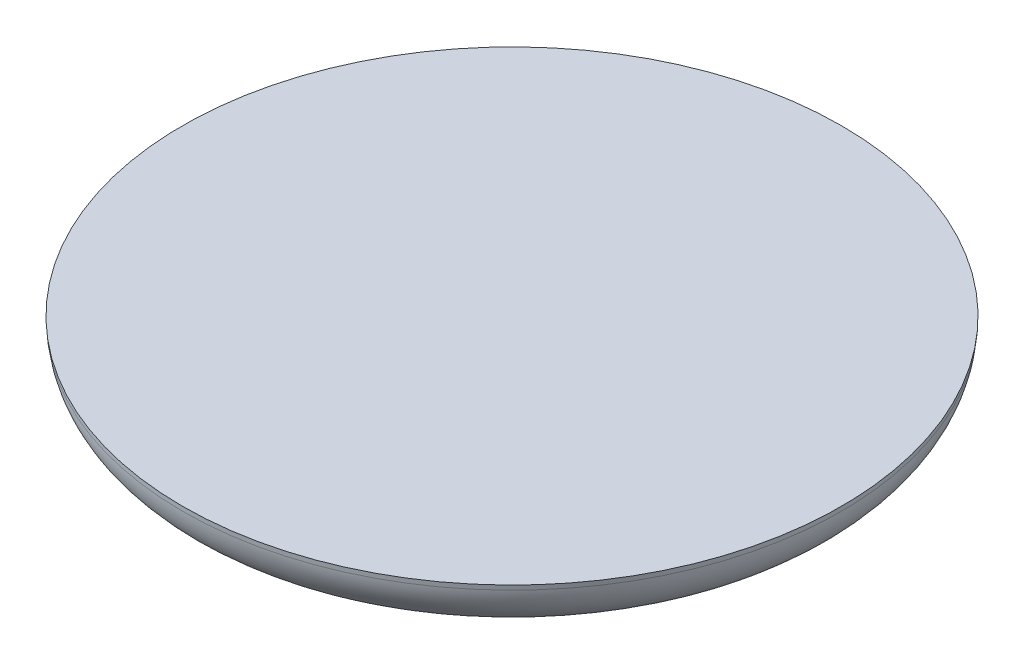
SolidWorks part; units mm, degrees
material "Water"
ref_plane "Front Plane" through (0, 0, 0) normal (0, 0, 1) x (1, 0, 0)
ref_plane "Top Plane" through (0, 0, 0) normal (0, 1, 0) x (1, 0, 0)
ref_plane "Right Plane" through (0, 0, 0) normal (1, 0, 0) x (0, 0, -1)
sketch "Sketch1" plane through (0, 0, 0) normal (0, 1, 0) x (1, 0, 0)
  circle A0 centre (0, 0) radius 38.1
extrude "Boss-Extrude1" add sketch "Sketch1" along normal blind 6.35 draft 5 draft outward yes
fillet "Fillet1" radius 6.35 1 edges at (0, 0, 38.1)
